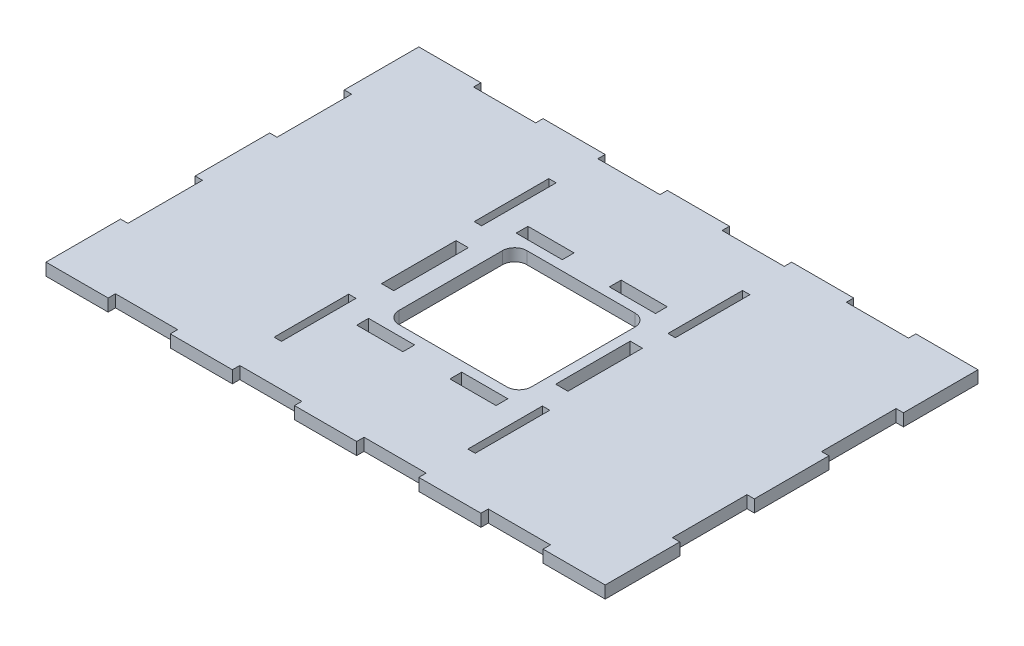
SolidWorks part; units mm, degrees
ref_plane "Front Plane" through (0, 0, 0) normal (0, 0, 1) x (1, 0, 0)
ref_plane "Top Plane" through (0, 0, 0) normal (0, 1, 0) x (1, 0, 0)
ref_plane "Right Plane" through (0, 0, 0) normal (1, 0, 0) x (0, 0, -1)
sketch "Sketch1" plane through (0, 0, 0) normal (0, 1, 0) x (1, 0, 0)
  line L0 (-38, -76) -> (-38, 76) construction
  line L1 (-114, -76) -> (114, -76) construction
  line L2 (-114, -76) -> (-114, 76) construction
  line L3 (-114, 76) -> (114, 76) construction
  line L4 (114, -76) -> (114, 76) construction
  line L5 (0, 76) -> (0, -76) construction
  line L6 (-114, 0) -> (-38, 0) construction
  line L7 (-114, 0) -> (-114, 15.2)
  line L8 (-114, 76) -> (-88.6667, 76)
  line L9 (-114, 76) -> (-114, 45.6)
  line L10 (-114, 45.6) -> (-111, 45.6)
  line L11 (-88.6667, 76) -> (-88.6667, 73)
  line L12 (-114, 15.2) -> (-111, 15.2)
  line L13 (-114, 0) -> (-38, 0)
  line L14 (-111, 15.2) -> (-111, 45.6)
  line L15 (-41, -76) -> (-41, 76) construction
  line L16 (-33, -76) -> (-33, 76) construction
  line L17 (-88.6667, 73) -> (-63.3333, 73)
  line L18 (-63.3333, 73) -> (-63.3333, 76)
  line L20 (0, 0) -> (0, 76)
  line L26 (0, 76) -> (-12.6667, 76)
  line L27 (-41, 56) -> (-38, 56)
  line L28 (-41, 56) -> (-41, 25.6)
  line L29 (-41, 25.6) -> (-38, 25.6)
  line L30 (-38, 56) -> (-38, 25.6)
  line L31 (-12.6667, 76) -> (-12.6667, 73)
  line L32 (-12.6667, 73) -> (-38, 73)
  line L33 (-38, 73) -> (-38, 76)
  line L34 (-38, 76) -> (-63.3333, 76)
  line L35 (-33, 0) -> (-33, 15.2)
  line L36 (-33, 15.2) -> (-38, 15.2)
  line L37 (-38, 15.2) -> (-38, 0)
  line L38 (-33, 0) -> (114, 0) construction
  line L39 (-33, 0) -> (0, 0)
  line L41 (-28.4, 30.1) -> (-9.6, 30.1)
  line L42 (-28.4, 30.1) -> (-28.4, 34.9)
  line L43 (-28.4, 34.9) -> (-9.6, 34.9)
  line L44 (-9.6, 30.1) -> (-9.6, 34.9)
  line L45 (-19, 34.9) -> (-19, 30.1) construction
  line L46 (-28.4, 32.5) -> (-9.6, 32.5) construction
  point P144 (-19, 32.5)
  point P192 (0, 0)
  dimension "D1" = 228
  dimension "D2" = 152
  dimension "D3" = 76
  dimension "D4" = 3
  dimension "D5" = 5
  dimension "D6" = 3
  dimension "D7" = 3
  dimension "D10" = 30.4
  dimension "D11" = 30.4
  dimension "D9" = 25.3333
  dimension "D12" = 25.3333
  dimension "D8" = 38
  dimension "D13" = 12.6667
  dimension "D14" = 20
  dimension "D15" = 56
  dimension "D16" = 30.4
  dimension "D17" = 15.2
  dimension "D18" = 18.8
  dimension "D21" = 4.8
  dimension "D20" = 32.5
  dimension "D19" = 19
extrude "Boss-Extrude1" add sketch "Sketch1" along normal blind 5
mirror "Mirror1" about plane through (-114, 5, 0) normal (0, 0, -1) of "Boss-Extrude1"
mirror "Mirror6" about plane through (0, 5, 0) normal (-1, 0, 0) of bodies 102
sketch "Sketch2" plane through (0, 5, 0) normal (0, 1, 0) x (1, 0, 0)
  line L0 (-28.4, 30.1) -> (-9.6, 30.1) construction
  line L1 (24, 26.1) -> (-20, 26.1)
  line L2 (29, 21.1) -> (29, -21.1)
  line L3 (24, -26.1) -> (-20, -26.1)
  line L4 (-25, 21.1) -> (-25, -21.1)
  line L5 (2, -26.1) -> (2, 26.1) construction
  line L6 (29, 0) -> (-25, 0) construction
  line L7 (-33, 15.2) -> (-33, -15.2) construction
  line L8 (33, 15.2) -> (33, -15.2) construction
  arc A0 (-20, -26.1) -> (-25, -21.1) centre (-20, -21.1) cw
  arc A1 (29, -21.1) -> (24, -26.1) centre (24, -21.1) cw
  arc A2 (24, 26.1) -> (29, 21.1) centre (24, 21.1) cw
  arc A3 (-20, 26.1) -> (-25, 21.1) centre (-20, 21.1) ccw
  point P176 (0, 0)
  dimension "D3" = 5
  dimension "D1" = 4
  dimension "D2" = 8
  dimension "D4" = 4
extrude "Cut-Extrude1" cut sketch "Sketch2" against normal through all contours L4 A0 L3 A1 L2 A2 L1 A3
equation "\"3mm akryyli\"= 3mm"
equation "\"5mm akryyli\"= 5mm"
equation "\"D6@Sketch1\"=\"3mm akryyli\""
equation "\"D7@Sketch1\"=\"3mm akryyli\""
equation "\"D1@Boss-Extrude1\"=\"5mm akryyli\""
equation "\"D4@Sketch1\"=\"3mm akryyli\""
equation "\"D5@Sketch1\"=\"5mm akryyli\""
